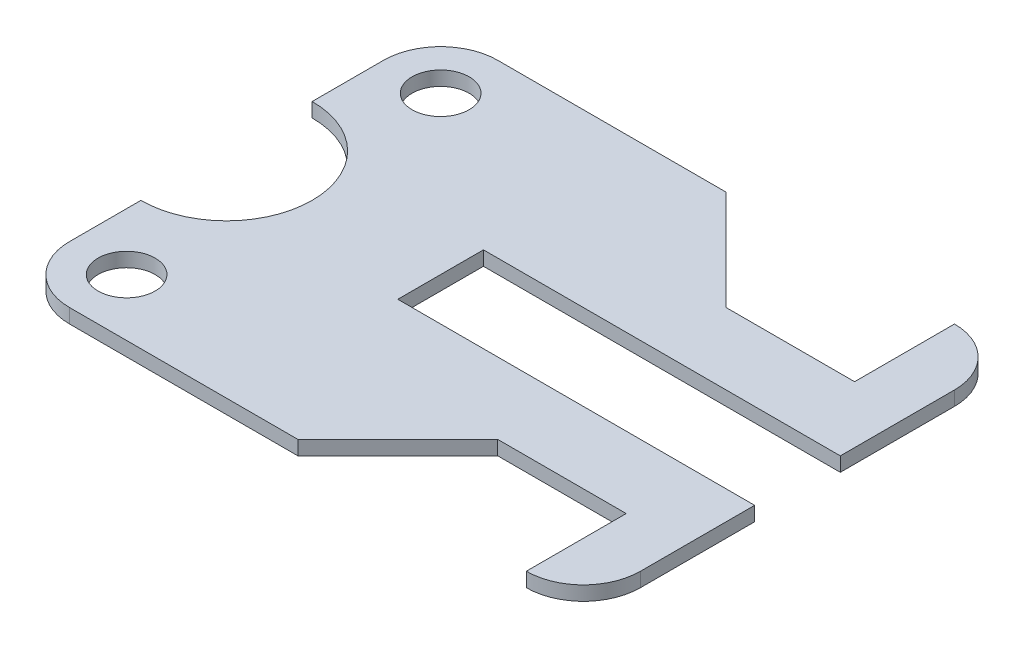
SolidWorks part; units mm, degrees
ref_plane "Front Plane" through (0, 0, 0) normal (0, 0, 1) x (1, 0, 0)
ref_plane "Top Plane" through (0, 0, 0) normal (0, 1, 0) x (1, 0, 0)
ref_plane "Right Plane" through (0, 0, 0) normal (1, 0, 0) x (0, 0, -1)
sketch "Sketch1" plane through (0, 0, 0) normal (0, 1, 0) x (1, 0, 0)
  line L0 (-20, 6) -> (-20, 11)
  line L1 (-16, -15) -> (0, -15)
  line L2 (-20, -11) -> (-20, -6)
  line L3 (-16, 15) -> (0, 15)
  line L4 (20, -11) -> (20, -3)
  line L5 (20, 3) -> (20, 11)
  line L6 (20, 3) -> (-5, 3)
  line L8 (20, -3) -> (-5, -3)
  line L9 (-5, 3) -> (-5, -3)
  line L10 (0, 15) -> (7, 8)
  line L11 (7, 8) -> (16, 8)
  line L12 (16, 8) -> (16, 15)
  line L13 (-20, 0) -> (22.3841, 0) construction
  line L14 (16, -8) -> (16, -15)
  line L15 (7, -8) -> (16, -8)
  line L16 (0, -15) -> (7, -8)
  arc A0 (-20, -6) -> (-20, 6) centre (-20, 0) ccw
  arc A1 (16, -15) -> (20, -11) centre (16, -11) ccw
  arc A2 (-16, -15) -> (-20, -11) centre (-16, -11) cw
  arc A3 (16, 15) -> (20, 11) centre (16, 11) cw
  arc A4 (-20, 11) -> (-16, 15) centre (-16, 11) cw
  circle A5 centre (-16, -11) radius 2
  circle A6 centre (-16, 11) radius 2
  point P10 (20, -15)
  point P15 (20, 15)
  dimension "D5" = 6
  dimension "D6" = 4
  dimension "D14" = 4
  dimension "D15" = 4
  dimension "D1" = 15
  dimension "D2" = 30
  dimension "D3" = 40
  dimension "D4" = 20
  dimension "D7" = 25
  dimension "D8" = 6
  dimension "D9" = 3
  dimension "D10" = 5
  dimension "D11" = 7
  dimension "D12" = 135
  dimension "D13" = 20
extrude "Boss-Extrude1" add sketch "Sketch1" along normal blind 1 contours L0 A4 L3 L10 L11 L12 A3 L5 L6 L9 L8 L4 A1 L14 L15 L16 L1 A2 L2 A0
